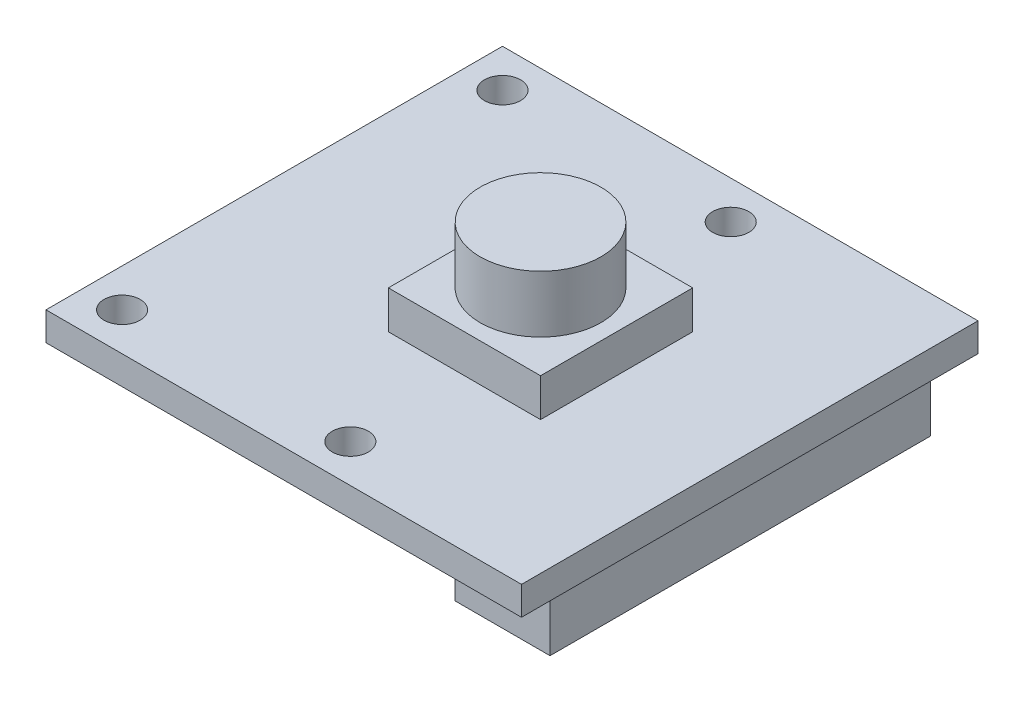
SolidWorks part; units mm, degrees
ref_plane "Front Plane" through (0, 0, 0) normal (0, 0, 1) x (1, 0, 0)
ref_plane "Top Plane" through (0, 0, 0) normal (0, 1, 0) x (1, 0, 0)
ref_plane "Right Plane" through (0, 0, 0) normal (1, 0, 0) x (0, 0, -1)
sketch "Sketch1" plane through (0, 0, 0) normal (0, 1, 0) x (1, 0, 0)
  line L1 (12.5, 12) -> (-12.5, 12)
  line L2 (12.5, 12) -> (12.5, -12)
  line L3 (12.5, -12) -> (-12.5, -12)
  line L4 (-12.5, 12) -> (-12.5, -12)
  line L5 (12.5, 12) -> (-12.5, -12) construction
  line L6 (12.5, -12) -> (-12.5, 12) construction
  point P0 (0, 0)
  dimension "D1" = 25
  dimension "D2" = 24
extrude "Boss-Extrude1" add sketch "Sketch1" along normal blind 1.5
sketch "Sketch2" plane through (0, 1.5, 0) normal (0, 1, 0) x (1, 0, 0)
  line L0 (-2.5, 4) -> (-12.5, 4) construction
  line L1 (-2.5, -4) -> (5.5, -4)
  line L2 (-2.5, -4) -> (-2.5, 4)
  line L3 (-2.5, 4) -> (5.5, 4)
  line L4 (5.5, -4) -> (5.5, 4)
  line L5 (-2.5, -4) -> (5.5, 4) construction
  line L6 (-2.5, 4) -> (5.5, -4) construction
  line L7 (-12.5, 12) -> (-12.5, -12) construction
  point P0 (1.5, 0)
  dimension "D1" = 10
  dimension "D2" = 8
extrude "Boss-Extrude2" add sketch "Sketch2" along normal blind 2
sketch "Sketch3" plane through (0, 3.5, 0) normal (0, 1, 0) x (1, 0, 0)
  line L0 (-2.5, 4) -> (-2.5, -4) construction
  line L1 (-2.5, -4) -> (5.5, -4) construction
  line L2 (-2.5, -4) -> (-2.5, 4) construction
  line L3 (-2.5, 4) -> (5.5, 4) construction
  line L4 (5.5, -4) -> (5.5, 4) construction
  line L5 (-2.5, -4) -> (5.5, 4) construction
  line L6 (-2.5, 4) -> (5.5, -4) construction
  line L7 (-2.5, -4) -> (5.5, -4) construction
  circle A0 centre (1.5, 0) radius 3.175
  dimension "D1" = 6.35
extrude "Boss-Extrude3" add sketch "Sketch3" along normal blind 3
sketch "Sketch5" plane through (0, 0, 0) normal (0, -1, 0) x (1, 0, 0)
  line L0 (12.5, 12) -> (12.5, -12) construction
  line L1 (7, 10) -> (12, 10)
  line L2 (7, 10) -> (7, -10)
  line L3 (7, -10) -> (12, -10)
  line L4 (12, 10) -> (12, -10)
  point P4 (7, 0)
  dimension "D1" = 5
  dimension "D2" = 0.5
  dimension "D3" = 20
extrude "Boss-Extrude4" add sketch "Sketch5" along normal blind 3
sketch "Sketch6" plane through (0, 1.5, 0) normal (0, 1, 0) x (1, 0, 0)
  line L0 (-10.5, 12) -> (-10.5, 10) construction
  line L1 (12.5, 12) -> (-12.5, 12) construction
  line L2 (-10.5, -10) -> (-10.5, -12) construction
  line L3 (-12.5, -12) -> (12.5, -12) construction
  line L4 (-10.5, 10) -> (-12.5, 10) construction
  line L5 (-12.5, 12) -> (-12.5, -12) construction
  circle A0 centre (-10.5, 10) radius 0.95
  circle A1 centre (1.5, 10) radius 0.95
  circle A2 centre (-10.5, -10) radius 0.95
  circle A3 centre (1.5, -10) radius 0.95
  dimension "D1" = 1.9
  dimension "D2" = 12
  dimension "D3" = 20
extrude "Cut-Extrude1" cut sketch "Sketch6" against normal up to next
